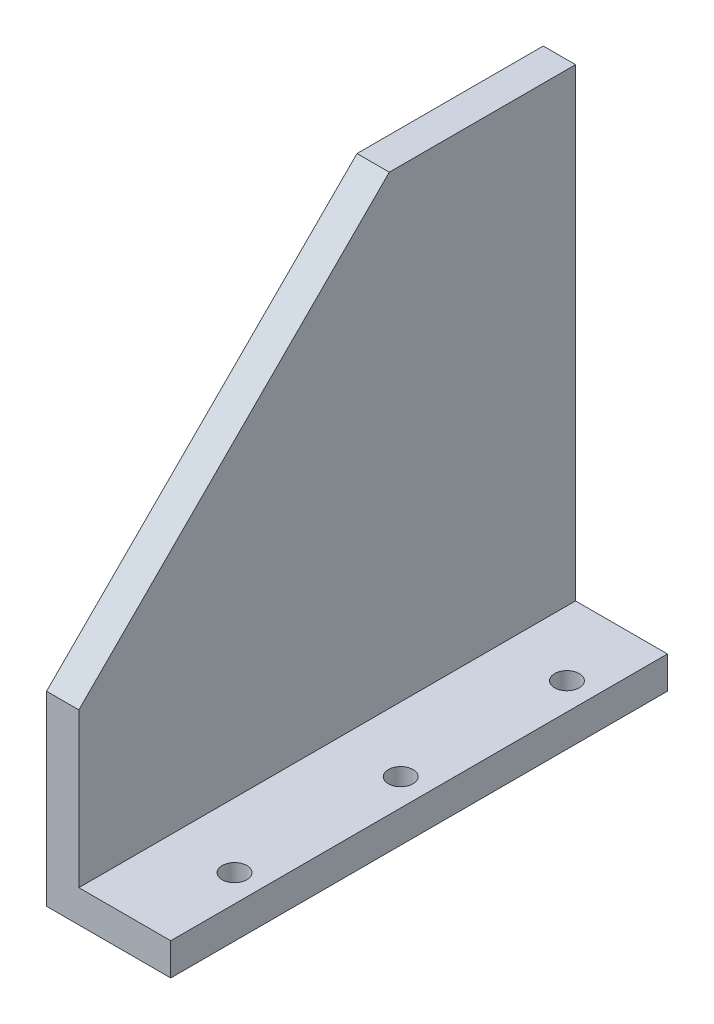
SolidWorks part; units mm, degrees
ref_plane "Front Plane" through (0, 0, 0) normal (0, 0, 1) x (1, 0, 0)
ref_plane "Top Plane" through (0, 0, 0) normal (0, 1, 0) x (1, 0, 0)
ref_plane "Right Plane" through (0, 0, 0) normal (1, 0, 0) x (0, 0, -1)
sketch "Sketch4" plane through (0, 0, 0) normal (0, 0, 1) x (1, 0, 0)
  line L0 (0, 0) -> (0, 50.8)
  line L1 (0, 50.8) -> (3.302, 50.8)
  line L2 (3.302, 50.8) -> (3.302, 3.302)
  line L3 (3.302, 3.302) -> (12.7, 3.302)
  line L4 (12.7, 3.302) -> (12.7, 0)
  line L5 (12.7, 0) -> (0, 0)
  dimension "D1" = 50.8
  dimension "D2" = 3.302
  dimension "D3" = 3.302
  dimension "D4" = 12.7
extrude "Boss-Extrude1" add sketch "Sketch4" along normal blind 50.8
hole_wizard "#39 (0.0995) Diameter Hole1" positions "Sketch5" profile "Sketch6" hole size "#39" standard "ANSI Inch" end condition through all
sketch "Sketch5" plane through (0, 0, 0) normal (0, -1, 0) x (-1, 0, 0)
  point P0 (-9.9296, -7.5079)
  point P3 (-9.9296, -24.5106)
  point P5 (-9.9296, -41.5079)
sketch "Sketch6" plane through (9.9296, 0, 7.5079) normal (1, 0, 0) x (0, 0, -1)
  line L0 (0, 0) -> (0, 50.8)
  line L1 (0, 50.8) -> (1.2636, 50.8)
  line L2 (1.2636, 50.8) -> (1.2636, 0)
  line L5 (1.2636, 0) -> (0, 0)
  line L11 (0, -6.35) -> (0, 107.95) construction
  dimension "Thru Hole Dia." = 2.5273
  dimension "Thru Hole Depth" = 50.8
sketch "Sketch7" plane through (0, 0, 0) normal (-1, 0, 0) x (0, 0, 1)
  line L0 (50.8, 50.8) -> (19.05, 50.8)
  line L1 (50.8, 50.8) -> (0, 50.8) construction
  line L2 (19.05, 50.8) -> (50.8, 19.05)
  line L3 (50.8, 50.8) -> (50.8, 0) construction
  line L4 (50.8, 19.05) -> (50.8, 50.8)
  dimension "D1" = 31.75
  dimension "D2" = 31.75
extrude "Cut-Extrude1" cut sketch "Sketch7" against normal up to surface (3.302 mm away) up to face at (3.302, 27.051, 25.4)
